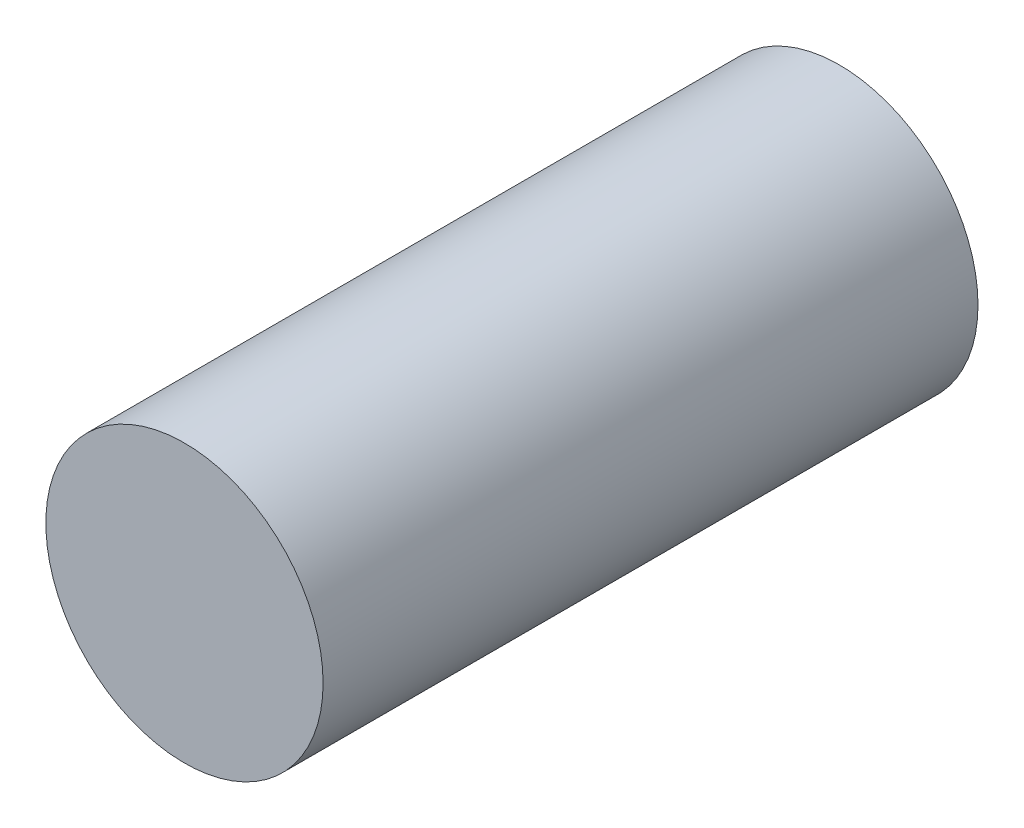
SolidWorks part; units mm, degrees
material "AISI 4130 Steel, annealed at 865C"
ref_plane "Front Plane" through (0, 0, 0) normal (0, 0, 1) x (1, 0, 0)
ref_plane "Top Plane" through (0, 0, 0) normal (0, 1, 0) x (1, 0, 0)
ref_plane "Right Plane" through (0, 0, 0) normal (1, 0, 0) x (0, 0, -1)
sketch "Sketch1" plane through (0, 0, 0) normal (0, 0, 1) x (1, 0, 0)
  circle A0 centre (0, 0) radius 12.7
  dimension "D1" = 25.4
extrude "Boss-Extrude1" add sketch "Sketch1" along normal blind 60
